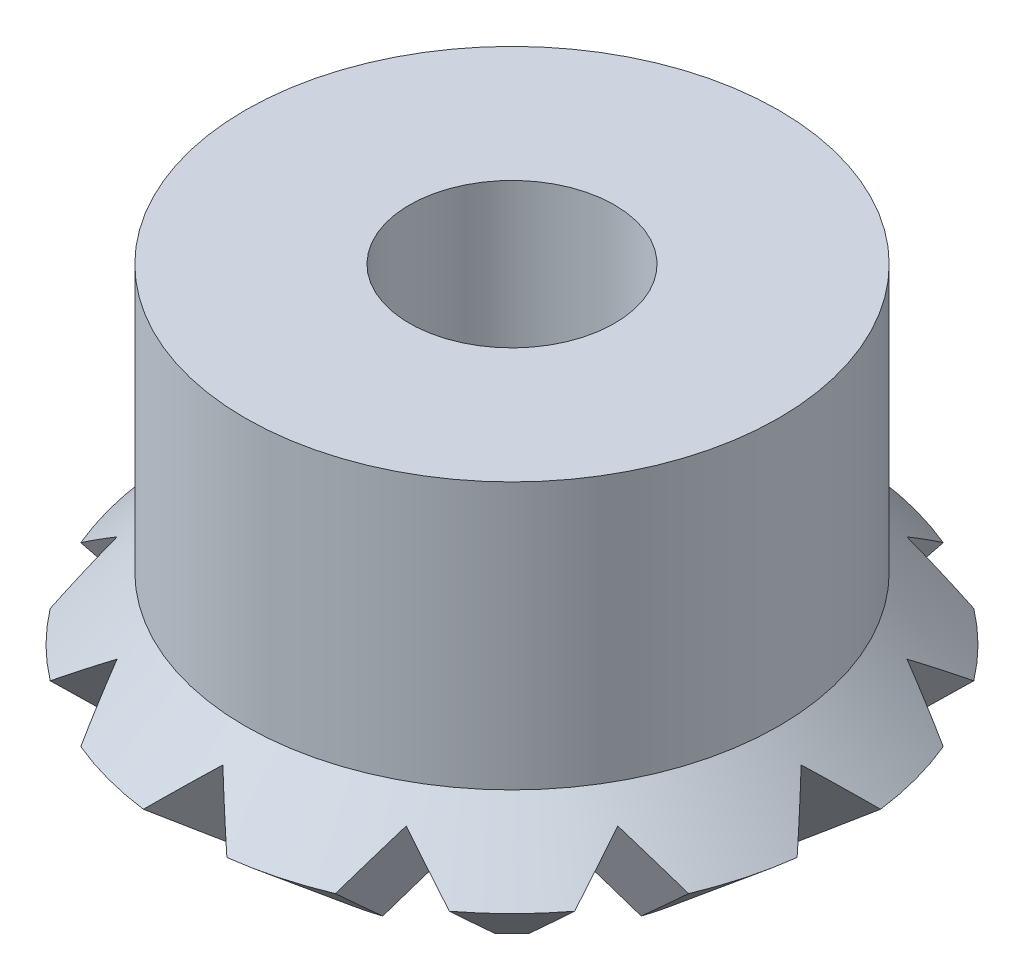
SolidWorks part; units mm, degrees
ref_plane "Front Plane" through (0, 0, 0) normal (1, 0, 0) x (0, 1, 0)
ref_plane "Top Plane" through (0, 0, 0) normal (0, 0, 1) x (0, 1, 0)
ref_plane "Right Plane" through (0, 0, 0) normal (0, 1, 0) x (-1, 0, 0)
sketch "Sketch2" plane through (0, 0, 0) normal (1, 0, 0) x (0, 1, 0)
  line L0 (-11.7435, 3.7552) -> (-14.8035, 6.8152)
  line L1 (-11.7435, 3.7552) -> (1.2565, 3.7552)
  line L4 (1.2565, 3.7552) -> (1.2565, -1.5598)
  line L5 (1.2565, -4.2448) -> (-17.7435, -4.2448)
  line L6 (1.2565, -4.2448) -> (1.2565, -1.5598)
  line L8 (-17.7435, -4.2448) -> (-17.7435, -1.5598)
  line L9 (-11.7435, 3.7552) -> (-10.6093, 2.621) construction
  line L10 (-14.8035, 6.8152) -> (-19.9672, 0.7049)
  line L11 (-14.8035, 6.8152) -> (-14.014, 6.8152) construction
  line L12 (-14.8035, 6.8152) -> (-16.5905, 6.8152) construction
  line L13 (-25.3915, -9.2448) -> (1.4719, -9.2448) construction
  line L14 (-19.9672, 0.7049) -> (-17.7435, -1.5598)
  dimension "D1" = 13
  dimension "D2" = 19
  dimension "D3" = 45
  dimension "D4" = 180
  dimension "D5" = 45
  dimension "D6" = 8
  dimension "D7" = 49.8
  dimension "D8" = 180
  dimension "D9" = 5
  dimension "D10" = 7.685
  dimension "D11" = 13
  dimension "D12" = 16.06
revolve "Revolve1" add sketch "Sketch2" angle 360 about L13
sketch "Sketch8" plane through (0, 0, 0) normal (1, 0, 0) x (0, 1, 0)
  line L0 (1.2565, -9.2448) -> (-28.7435, -9.2448) construction
  line L1 (1.2565, -22.2448) -> (1.2565, 3.7552) construction
  line L2 (1.2565, -9.2448) -> (1.2565, 3.7552) construction
  line L3 (1.2565, 3.7552) -> (-11.7435, 3.7552) construction
  line L7 (-28.7435, -9.2448) -> (-15.0534, 6.9553)
  line L8 (-14.8035, 6.8152) -> (-19.9672, 0.7049) construction
  dimension "D1" = 0
  dimension "D2" = 30
  dimension "D3" = 90
  dimension "D4" = 0
  dimension "D5" = 13
  dimension "D6" = 21.21
ref_plane "Plane1" through (0, 0, -9.2448) normal (0, 0, 1) x (1, 0, 0)
sketch "Sketch9" plane through (0, 0, -9.2448) normal (0, 0, 1) x (1, 0, 0)
  line L0 (3.4641, -30.7435) -> (0, -24.7435)
  line L1 (0, -24.7435) -> (-3.4641, -30.7435)
  line L2 (-3.4641, -30.7435) -> (3.4641, -30.7435)
  line L3 (0, 1.2565) -> (0, -28.7435) construction
  point P3 (0.8417, -27.7435)
  point P4 (0.1258, -27.7515)
  dimension "D1" = 60
  dimension "D2" = 60
  dimension "D3" = 4
  dimension "D4" = 4
  dimension "D5" = 4
sweep "Cut-Sweep1" cut profiles "Sketch9" path "Sketch8"
pattern_circular "CirPattern1" count 12 over 360 about axis through (0, 0, -9.2448) along (0, 1, 0) of "Cut-Sweep1"
